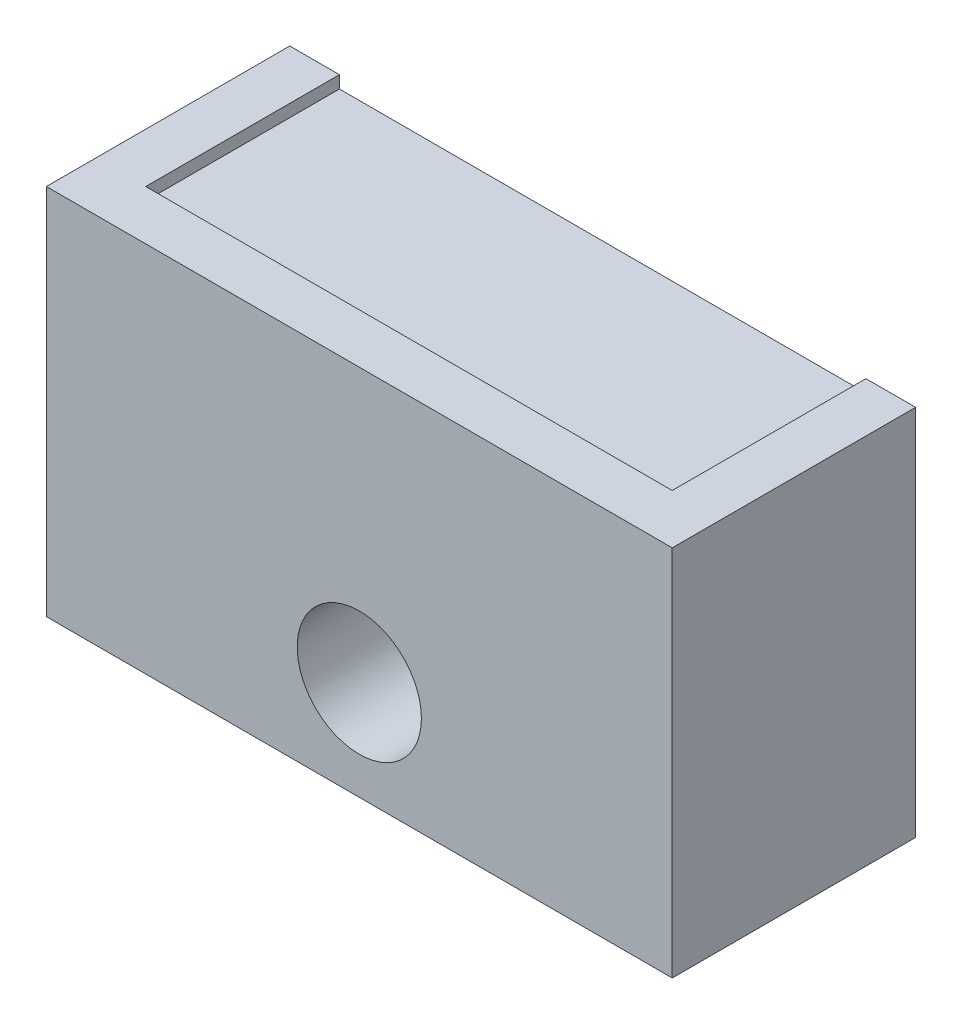
SolidWorks part; units mm, degrees
ref_plane "Plan de face" through (0, 0, 0) normal (0, 0, 1) x (1, 0, 0)
ref_plane "Plan de dessus" through (0, 0, 0) normal (0, 1, 0) x (1, 0, 0)
ref_plane "Plan de droite" through (0, 0, 0) normal (1, 0, 0) x (0, 0, -1)
sketch "Sketch2" plane through (0, 0, 0) normal (0, 0, 1) x (1, 0, 0)
  line L1 (0, 0) -> (-25.2, 0)
  line L2 (0, 0) -> (0, 15)
  line L3 (0, 15) -> (-25.2, 15)
  line L4 (-25.2, 0) -> (-25.2, 15)
  dimension "D1" = 25.2
  dimension "D2" = 15
extrude "Boss-Extrude2" add sketch "Sketch2" along normal blind 2
sketch "Sketch3" plane through (0, 0, 0) normal (0, 0, -1) x (-1, 0, 0)
  line L0 (25.2, 0) -> (0, 0) construction
  line L1 (0, 15) -> (2, 15)
  line L2 (0, 15) -> (0, 0)
  line L3 (0, 0) -> (2, 0)
  line L4 (2, 15) -> (2, 0)
  line L5 (0, 15) -> (25.2, 15) construction
  line L6 (25.2, 0) -> (23.2, 0)
  line L7 (25.2, 0) -> (25.2, 15)
  line L8 (25.2, 15) -> (23.2, 15)
  line L9 (23.2, 0) -> (23.2, 15)
  line L11 (2, 15) -> (23.2, 15)
  line L12 (2, 15) -> (2, 13)
  line L13 (2, 13) -> (23.2, 13)
  line L14 (23.2, 15) -> (23.2, 13)
  line M3 (0, 15) -> (0, 0)
  line M4 (0, 0) -> (25.2, 0)
  line M5 (25.2, 0) -> (25.2, 15)
  line M6 (25.2, 15) -> (0, 15)
  dimension "D1" = 2
  dimension "D2" = 2
  dimension "D3" = 2
extrude "Boss-Extrude3" add sketch "Sketch3" along normal blind 7.8 contours L4 M6 M3 M4 | L4 L13 L9 M6 | L9 M4 M5 M6
sketch "Sketch8" plane through (0, 0, 0) normal (0, 0, -1) x (-1, 0, 0)
  line L0 (23.2, 0) -> (23.2, 13) construction
  line L1 (2, 0) -> (23.2, 0)
  line L2 (2, 0) -> (2, 8.1631)
  line L3 (2, 8.1631) -> (23.2, 8.1631)
  line L4 (23.2, 0) -> (23.2, 8.1631)
  line L5 (23.2, 8.1631) -> (2, 8.1631) construction
  line L7 (4.35, 8.1631) -> (2, 8.1631)
  line L8 (4.35, 8.1631) -> (4.35, 0)
  line L9 (4.35, 0) -> (2, 0)
  line L10 (2, 8.1631) -> (2, 0)
  line L11 (9.35, 8.1631) -> (15.8479, 8.1631)
  line L12 (9.35, 8.1631) -> (9.35, 0)
  line L13 (9.35, 0) -> (15.8479, 0)
  line L14 (15.8479, 8.1631) -> (15.8479, 0)
  line L15 (20.85, 8.1631) -> (23.2, 8.1631)
  line L16 (20.85, 8.1631) -> (20.85, 0)
  line L17 (20.85, 0) -> (23.2, 0)
  line L18 (23.2, 8.1631) -> (23.2, 0)
  line M10 (2, 13) -> (2, 0)
  line M11 (2, 0) -> (23.2, 0)
  line M12 (23.2, 0) -> (23.2, 13)
  dimension "D1" = 6.4979
  dimension "D2" = 2.35
  dimension "D3" = 2.35
  dimension "D4" = 5
  dimension "D5" = 5.0021
  dimension "D6" = 8.1631
extrude "Boss-Extrude6" add sketch "Sketch8" along normal blind 7.8 contours L8 L3 M10 M11 | L14 L3 L12 M11 | L3 L16 M11 M12
sketch "Sketch9" plane through (0, 0, 0) normal (0, 0, -1) x (-1, 0, 0)
  line L1 (4.35, 8.1631) -> (9.35, 8.1631)
  line L2 (4.35, 8.1631) -> (4.35, 0)
  line L3 (4.35, 0) -> (9.35, 0)
  line L4 (9.35, 8.1631) -> (9.35, 0)
  line L5 (15.8479, 8.1631) -> (20.85, 8.1631)
  line L6 (15.8479, 8.1631) -> (15.8479, 0)
  line L7 (15.8479, 0) -> (20.85, 0)
  line L8 (20.85, 8.1631) -> (20.85, 0)
extrude "Boss-Extrude7" add sketch "Sketch9" along normal blind 1.3
sketch "Sketch10" plane through (0, 15, 0) normal (0, 1, 0) x (1, 0, 0)
  line L0 (0, -2) -> (-25.2, -2) construction
  line L1 (-2, 7.8) -> (-23.2, 7.8)
  line L2 (-2, 7.8) -> (-2, 0)
  line L3 (-2, 0) -> (-23.2, 0)
  line L4 (-23.2, 7.8) -> (-23.2, 0)
  line L5 (-25.2, -2) -> (-25.2, 7.8) construction
  dimension "D1" = 2
  dimension "D2" = 2
extrude "Cut-Extrude3" cut sketch "Sketch10" against normal blind 0.5
sketch "Sketch12" plane through (0, 0, 2) normal (0, 0, 1) x (1, 0, 0)
  line L1 (0, 0) -> (0, 15) construction
  line L2 (-25.2, 0) -> (0, 0) construction
  circle A0 centre (-12.6, 4) radius 1
  dimension "D1" = 2
  dimension "D2" = 12.6
  dimension "D3" = 4
extrude "Cut-Extrude4" cut sketch "Sketch12" against normal through all
sketch "Sketch13" plane through (0, 0, 2) normal (0, 0, 1) x (1, 0, 0)
  circle A0 centre (-12.6, 4) radius 2.5
  dimension "D1" = 5
extrude "Cut-Extrude5" cut sketch "Sketch13" against normal blind 5.6348
